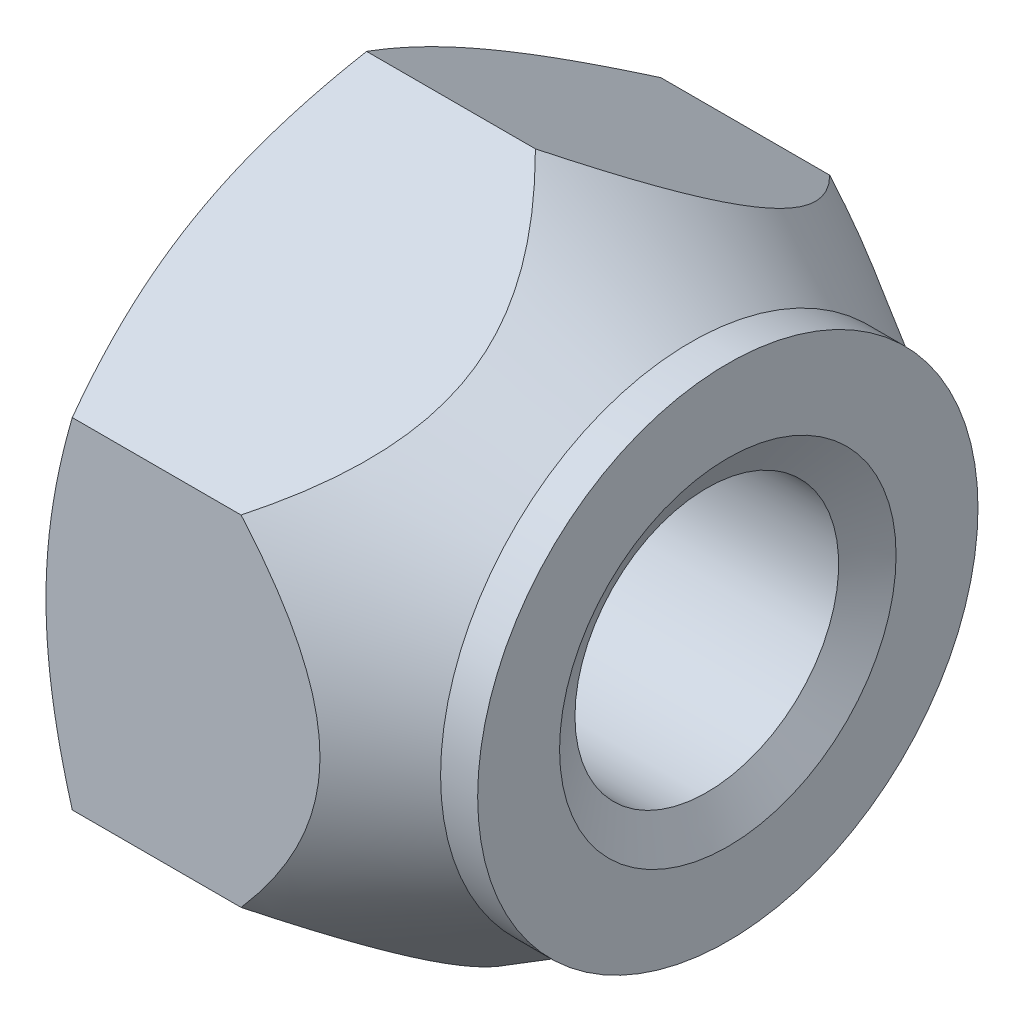
SolidWorks part; units mm, degrees
ref_plane "Front Plane" through (0, 0, 0) normal (0, 0, 1) x (1, 0, 0)
ref_plane "Top Plane" through (0, 0, 0) normal (0, 1, 0) x (1, 0, 0)
ref_plane "Right Plane" through (0, 0, 0) normal (1, 0, 0) x (0, 0, -1)
ref_plane "Plane1"
sketch "Sketch1" plane through (0, 0, 0) normal (1, 0, 0) x (0, 1, 0)
  line L0 (-6.4158, 0) -> (-3.2079, 5.5562)
  line L1 (-3.2079, 5.5562) -> (3.2079, 5.5563)
  line L2 (3.2079, 5.5563) -> (6.4158, 0)
  line L3 (6.4158, 0) -> (3.2079, -5.5562)
  line L4 (3.2079, -5.5562) -> (-3.2079, -5.5563)
  line L5 (-3.2079, -5.5563) -> (-6.4158, 0)
  dimension "D1" = 12.8316
extrude "Body" add sketch "Sketch1" along normal blind 7.3152
hole_wizard "Thread" positions "Sketch3" profile "Sketch2" legacy end condition through all
sketch "Sketch3" plane through (0, 0, 0) normal (-1, 0, 0) x (0, 0, 1)
  point P1 (0, 0)
sketch "Sketch2" plane through (0, 0, 0) normal (0, 1, 0) x (0, 0, 1)
  line L0 (0, 0) -> (0, 7.3152)
  line L1 (0, 7.3152) -> (2.4892, 7.3152)
  line L2 (2.4892, 7.3152) -> (2.4892, 0)
  line L3 (2.4892, 0) -> (0, 0)
  line L4 (0, 110) -> (0, -10) construction
  dimension "Diameter" = 4.9784
  dimension "Depth" = 7.3152
cosmetic thread "Cosmetic Thread1"
chamfer "Chamfer1" distance 0.6874 angle 30 1 edges at (0, 0, 2.4892)
chamfer "Chamfer2" distance 0.6874 angle 30 1 edges at (7.3152, 0, 2.4892)
ref_plane "Plane2"
sketch "Sketch4" plane through (0, 0, 0) normal (0, 0, 1) x (1, 0, 0)
  line L0 (0, 6.4158) -> (0, 5.5563)
  line L1 (0, 5.5563) -> (0.4963, 6.4158)
  line L2 (0.4963, 6.4158) -> (0, 6.4158)
  line L3 (-1.463, 0) -> (8.7782, 0) construction
  line L4 (3.683, 6.4158) -> (6.6153, 4.7228)
  line L5 (6.6153, 4.7228) -> (7.3152, 4.7228)
  line L6 (7.3152, 4.7228) -> (7.3152, 6.4158)
  line L7 (7.3152, 6.4158) -> (3.683, 6.4158)
  line L8 (0, 6.4158) -> (0, 3.2079) construction
  dimension "D1" = 150
  dimension "D2" = 90
  dimension "D3" = 4.7228
  dimension "D4" = 150
  dimension "D5" = 120
revolve "Chamfer3" cut sketch "Sketch4" angle 360 about L3
